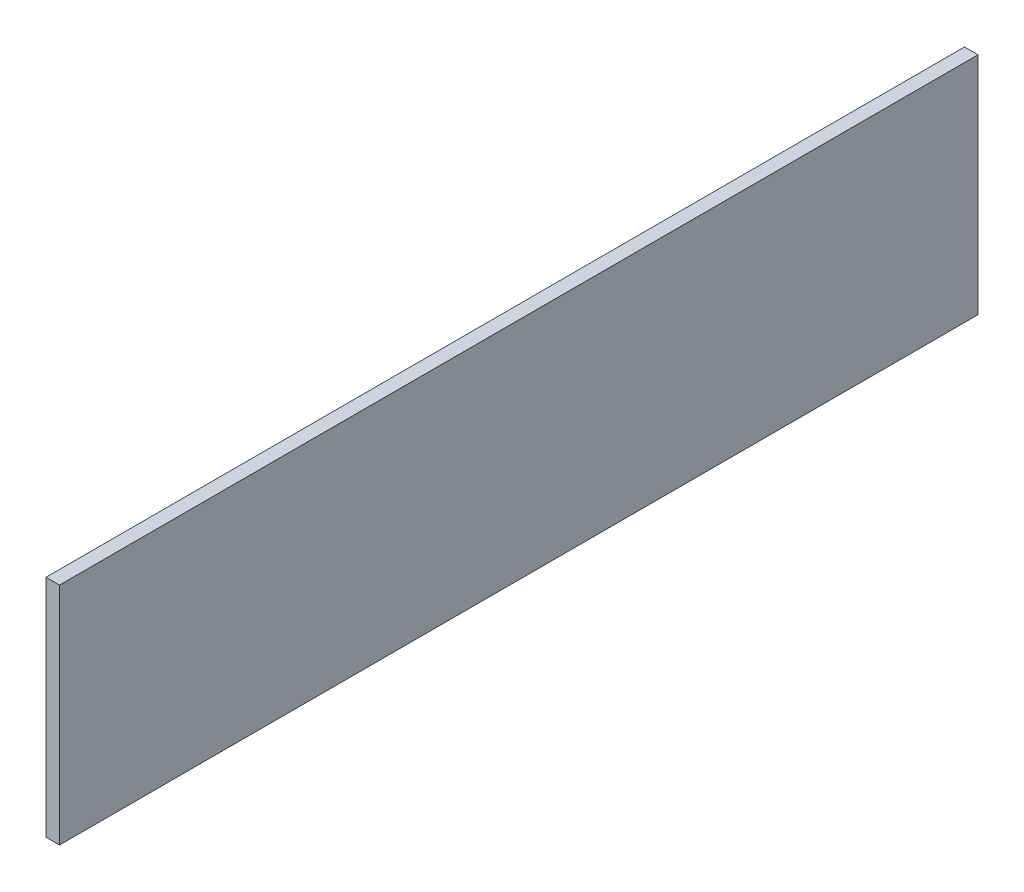
SolidWorks part; units mm, degrees
ref_plane "Front Plane" through (0, 0, 0) normal (0, 0, 1) x (1, 0, 0)
ref_plane "Top Plane" through (0, 0, 0) normal (0, 1, 0) x (1, 0, 0)
ref_plane "Right Plane" through (0, 0, 0) normal (1, 0, 0) x (0, 0, -1)
sketch "Sketch1" plane through (0, 0, 0) normal (1, 0, 0) x (0, 0, -1)
  line L1 (-51.4933, 43.7667) -> (152.5067, 43.7667)
  line L2 (-51.4933, 43.7667) -> (-51.4933, -6.2333)
  line L3 (-51.4933, -6.2333) -> (152.5067, -6.2333)
  line L4 (152.5067, 43.7667) -> (152.5067, -6.2333)
  dimension "D1" = 204
  dimension "D2" = 50
extrude "Boss-Extrude2" add sketch "Sketch1" along normal blind 3
